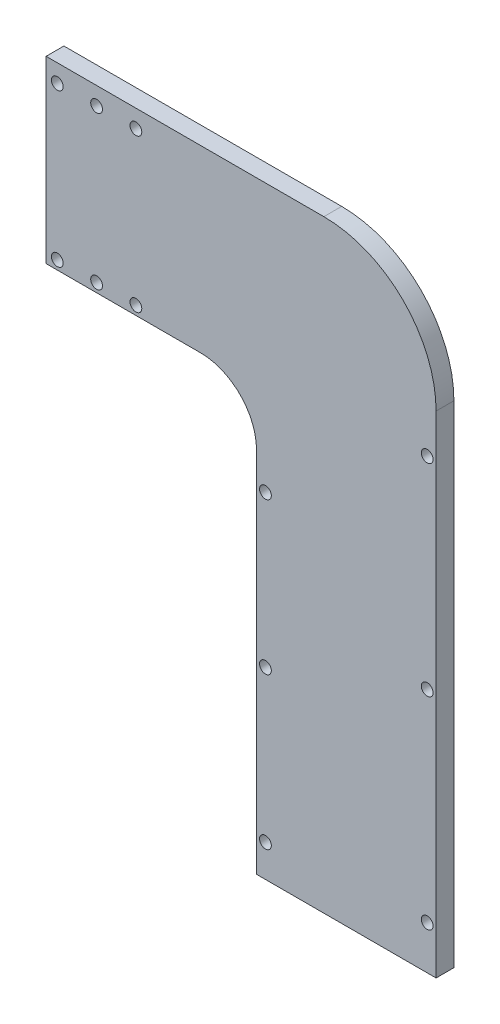
SolidWorks part; units mm, degrees
ref_plane "Front Plane" through (0, 0, 0) normal (0, 0, 1) x (1, 0, 0)
ref_plane "Top Plane" through (0, 0, 0) normal (0, 1, 0) x (1, 0, 0)
ref_plane "Right Plane" through (0, 0, 0) normal (1, 0, 0) x (0, 0, -1)
sketch "Sketch1" plane through (0, 0, 0) normal (0, 0, 1) x (1, 0, 0)
  line L0 (-69.5, 107.5) -> (-69.5, 43.5)
  line L1 (-69.5, -107.5) -> (69.5, -107.5) construction
  line L2 (-69.5, -107.5) -> (-69.5, 107.5) construction
  line L3 (-69.5, 107.5) -> (69.5, 107.5)
  line L4 (69.5, -107.5) -> (69.5, 107.5)
  line L5 (-69.5, -107.5) -> (69.5, 107.5) construction
  line L6 (-69.5, 107.5) -> (69.5, -107.5) construction
  line L7 (-69.5, 43.5) -> (5.5, 43.5)
  line L8 (5.5, 43.5) -> (5.5, -107.5)
  line L9 (5.5, -107.5) -> (69.5, -107.5)
  point P0 (0, 0)
  dimension "D1" = 139
  dimension "D2" = 215
  dimension "D3" = 64
  dimension "D4" = 75
extrude "Boss-Extrude1" add sketch "Sketch1" along normal mid plane 6.35 contours L3 L4 L9 L8 L7 L0
fillet "Fillet2" radius 40 1 edges at (69.5, 107.5, 0)
fillet "Fillet3" radius 20 1 edges at (5.5, 43.5, 0)
sketch "Sketch2" plane through (0, 0, 3.175) normal (0, 0, 1) x (1, 0, 0)
  line L0 (-65.5, 101.15) -> (-37.5, 101.15) construction
  line L1 (-69.5, 107.5) -> (29.5, 107.5) construction
  line L2 (-69.5, 107.5) -> (-69.5, 43.5) construction
  line L3 (-65.5, 46.675) -> (-37.5, 46.675) construction
  line L4 (-69.5, 43.5) -> (-14.5, 43.5) construction
  circle A0 centre (-65.5, 101.15) radius 2.1
  circle A1 centre (-37.5, 101.15) radius 2.1
  circle A2 centre (-51.5, 101.15) radius 2.1
  circle A6 centre (-65.5, 46.675) radius 2.1
  circle A7 centre (-37.5, 46.675) radius 2.1
  circle A8 centre (-51.5, 46.675) radius 2.1
  dimension "D2" = 4.2
  dimension "D3" = 4.2
  dimension "D4" = 4.2
  dimension "D8" = 4.2
  dimension "D9" = 4.2
  dimension "D10" = 4.2
  dimension "D1" = 28
  dimension "D5" = 6.35
  dimension "D6" = 4
  dimension "D7" = 28
  dimension "D11" = 3.175
  dimension "D12" = 4
extrude "Cut-Extrude1" cut sketch "Sketch2" against normal through all
sketch "Sketch3" plane through (0, 0, 3.175) normal (0, 0, 1) x (1, 0, 0)
  line L0 (66.325, 52) -> (66.325, -92) construction
  line L1 (5.5, -107.5) -> (69.5, -107.5) construction
  line L2 (69.5, -107.5) -> (69.5, 67.5) construction
  circle A0 centre (66.325, -92) radius 2.1
  circle A1 centre (66.325, 52) radius 2.1
  circle A2 centre (66.325, -20) radius 2.1
  dimension "D2" = 4.2
  dimension "D3" = 4.2
  dimension "D4" = 4.2
  dimension "D1" = 144
  dimension "D5" = 15.5
  dimension "D6" = 3.175
extrude "Cut-Extrude2" cut sketch "Sketch3" against normal through all contours A0 | A2 | A1
sketch "Sketch4" plane through (0, 0, 3.175) normal (0, 0, 1) x (1, 0, 0)
  line L0 (8.675, 12) -> (8.675, -96)
  line L1 (5.5, -107.5) -> (69.5, -107.5) construction
  line L2 (5.5, 23.5) -> (5.5, -107.5) construction
  circle A0 centre (8.675, -96) radius 2.1
  circle A1 centre (8.675, -42) radius 2.1
  circle A2 centre (8.675, 12) radius 2.1
  dimension "D4" = 4.2
  dimension "D5" = 4.2
  dimension "D6" = 4.2
  dimension "D1" = 108
  dimension "D2" = 11.5
  dimension "D3" = 3.175
extrude "Cut-Extrude3" cut sketch "Sketch4" against normal through all contours A0 | A1 | A2
